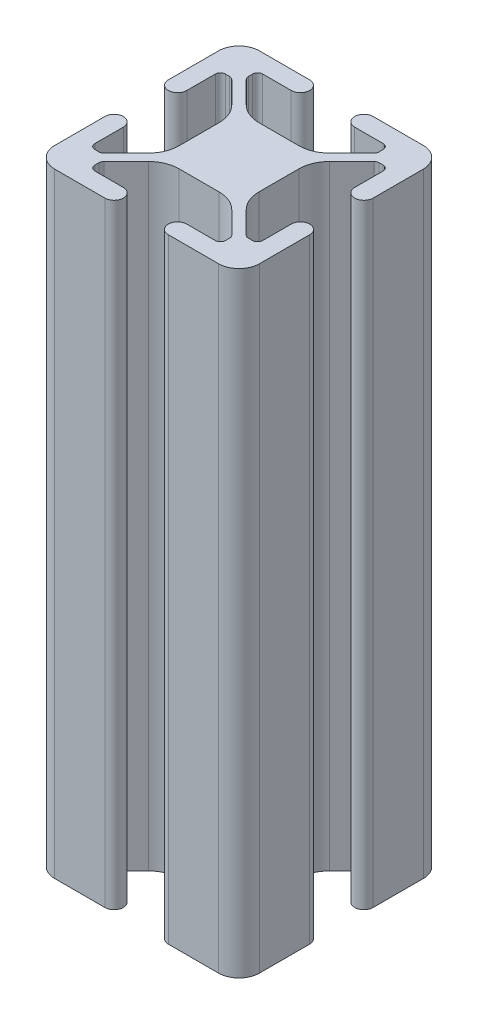
SolidWorks part; units mm, degrees
ref_plane "前视基准面" through (0, 0, 0) normal (0, 0, 1) x (1, 0, 0)
ref_plane "上视基准面" through (0, 0, 0) normal (0, 1, 0) x (1, 0, 0)
ref_plane "右视基准面" through (0, 0, 0) normal (1, 0, 0) x (0, 0, -1)
sketch "草图1" plane through (0, 0, 0) normal (0, 1, 0) x (1, 0, 0)
  line L0 (-1.0428, -10.0859) -> (3.8572, -10.0859)
  line L1 (1.0762, -11.8859) -> (3.8572, -11.8859)
  line L2 (2.8854, -15.3072) -> (0.7226, -13.1443)
  line L3 (2.1786, -16.0141) -> (0.0157, -13.8512)
  line L4 (-3.0428, -12.0859) -> (-3.0428, -16.9859)
  line L5 (-1.2428, -14.2048) -> (-1.2428, -16.9859)
  line L6 (-0.7428, -13.7048) -> (-0.3378, -13.7048)
  line L7 (0.5762, -12.3859) -> (0.5762, -12.7908)
  line L8 (-1.0428, -30.0859) -> (3.8572, -30.0859)
  line L9 (1.0762, -28.2859) -> (3.8572, -28.2859)
  line L10 (2.8854, -24.8645) -> (0.7226, -27.0274)
  line L11 (2.1786, -24.1577) -> (0.0157, -26.3205)
  line L12 (-3.0428, -28.0859) -> (-3.0428, -23.1859)
  line L13 (-1.2428, -25.9669) -> (-1.2428, -23.1859)
  line L14 (-0.7428, -26.4669) -> (-0.3378, -26.4669)
  line L15 (0.5762, -27.7859) -> (0.5762, -27.3809)
  line L16 (14.9572, -10.0859) -> (10.0572, -10.0859)
  line L17 (12.8383, -11.8859) -> (10.0572, -11.8859)
  line L18 (11.029, -15.3072) -> (13.1919, -13.1443)
  line L19 (11.7359, -16.0141) -> (13.8988, -13.8512)
  line L20 (16.9572, -12.0859) -> (16.9572, -16.9859)
  line L21 (15.1572, -14.2048) -> (15.1572, -16.9859)
  line L22 (14.6572, -13.7048) -> (14.2523, -13.7048)
  line L23 (13.3383, -12.3859) -> (13.3383, -12.7908)
  line L24 (14.9572, -30.0859) -> (10.0572, -30.0859)
  line L25 (12.8383, -28.2859) -> (10.0572, -28.2859)
  line L26 (11.029, -24.8645) -> (13.1919, -27.0274)
  line L27 (11.7359, -24.1577) -> (13.8988, -26.3205)
  line L28 (16.9572, -28.0859) -> (16.9572, -23.1859)
  line L29 (15.1572, -25.9669) -> (15.1572, -23.1859)
  line L30 (14.6572, -26.4669) -> (14.2523, -26.4669)
  line L31 (13.3383, -27.7859) -> (13.3383, -27.3809)
  line L32 (5.0068, -16.1859) -> (8.9077, -16.1859)
  line L33 (10.8572, -18.1354) -> (10.8572, -22.0363)
  line L34 (3.0572, -18.1354) -> (3.0572, -22.0363)
  line L35 (5.0068, -23.9859) -> (8.9077, -23.9859)
  circle A0 centre (6.9572, -20.0859) radius 2.5
  arc A1 (2.8854, -15.3072) -> (5.0068, -16.1859) centre (5.0068, -13.1859) ccw
  arc A2 (3.0572, -18.1354) -> (2.1786, -16.0141) centre (0.0572, -18.1354) ccw
  arc A3 (3.8572, -11.8859) -> (3.8572, -10.0859) centre (3.8572, -10.9859) ccw
  arc A4 (0.5762, -12.7908) -> (0.7226, -13.1443) centre (1.0762, -12.7908) ccw
  arc A5 (0.0157, -13.8512) -> (-0.3378, -13.7048) centre (-0.3378, -14.2048) ccw
  arc A6 (-3.0428, -16.9859) -> (-1.2428, -16.9859) centre (-2.1428, -16.9859) ccw
  arc A7 (-1.0428, -10.0859) -> (-3.0428, -12.0859) centre (-1.0428, -12.0859) ccw
  arc A8 (-0.7428, -13.7048) -> (-1.2428, -14.2048) centre (-0.7428, -14.2048) ccw
  arc A9 (1.0762, -11.8859) -> (0.5762, -12.3859) centre (1.0762, -12.3859) ccw
  arc A10 (5.0068, -23.9859) -> (2.8854, -24.8645) centre (5.0068, -26.9859) ccw
  arc A11 (2.1786, -24.1577) -> (3.0572, -22.0363) centre (0.0572, -22.0363) ccw
  arc A12 (3.8572, -30.0859) -> (3.8572, -28.2859) centre (3.8572, -29.1859) ccw
  arc A13 (0.7226, -27.0274) -> (0.5762, -27.3809) centre (1.0762, -27.3809) ccw
  arc A14 (-0.3378, -26.4669) -> (0.0157, -26.3205) centre (-0.3378, -25.9669) ccw
  arc A15 (-1.2428, -23.1859) -> (-3.0428, -23.1859) centre (-2.1428, -23.1859) ccw
  arc A16 (-3.0428, -28.0859) -> (-1.0428, -30.0859) centre (-1.0428, -28.0859) ccw
  arc A17 (-1.2428, -25.9669) -> (-0.7428, -26.4669) centre (-0.7428, -25.9669) ccw
  arc A18 (0.5762, -27.7859) -> (1.0762, -28.2859) centre (1.0762, -27.7859) ccw
  arc A19 (8.9077, -16.1859) -> (11.029, -15.3072) centre (8.9077, -13.1859) ccw
  arc A20 (11.7359, -16.0141) -> (10.8572, -18.1354) centre (13.8572, -18.1354) ccw
  arc A21 (10.0572, -10.0859) -> (10.0572, -11.8859) centre (10.0572, -10.9859) ccw
  arc A22 (13.1919, -13.1443) -> (13.3383, -12.7908) centre (12.8383, -12.7908) ccw
  arc A23 (14.2523, -13.7048) -> (13.8988, -13.8512) centre (14.2523, -14.2048) ccw
  arc A24 (15.1572, -16.9859) -> (16.9572, -16.9859) centre (16.0572, -16.9859) ccw
  arc A25 (16.9572, -12.0859) -> (14.9572, -10.0859) centre (14.9572, -12.0859) ccw
  arc A26 (15.1572, -14.2048) -> (14.6572, -13.7048) centre (14.6572, -14.2048) ccw
  arc A27 (13.3383, -12.3859) -> (12.8383, -11.8859) centre (12.8383, -12.3859) ccw
  arc A28 (11.029, -24.8645) -> (8.9077, -23.9859) centre (8.9077, -26.9859) ccw
  arc A29 (10.8572, -22.0363) -> (11.7359, -24.1577) centre (13.8572, -22.0363) ccw
  arc A30 (10.0572, -28.2859) -> (10.0572, -30.0859) centre (10.0572, -29.1859) ccw
  arc A31 (13.3383, -27.3809) -> (13.1919, -27.0274) centre (12.8383, -27.3809) ccw
  arc A32 (13.8988, -26.3205) -> (14.2523, -26.4669) centre (14.2523, -25.9669) ccw
  arc A33 (16.9572, -23.1859) -> (15.1572, -23.1859) centre (16.0572, -23.1859) ccw
  arc A34 (14.9572, -30.0859) -> (16.9572, -28.0859) centre (14.9572, -28.0859) ccw
  arc A35 (14.6572, -26.4669) -> (15.1572, -25.9669) centre (14.6572, -25.9669) ccw
  arc A36 (12.8383, -28.2859) -> (13.3383, -27.7859) centre (12.8383, -27.7859) ccw
extrude "凸台-拉伸1" add sketch "草图1" along normal blind 60 contours L32 A19 L18 A22 L23 A27 L17 A21 L16 A25 L20 A24 L21 A26 L22 A23 L19 A20 L33 A29 L27 A32 L30 A35 L29 A33 L28 A34 L24 A30 L25 A36 L31 A31 L26 A28 L35 A10 L10 A13 L15 A18 L9 A12 L8 A16 L12 A15 L13 A17 L14 A14 L11 A11 L34 A2 L3 A5 L6 A8 L5 A6 L4 A7 L0 A3 L1 A9 L7 A4 L2 A1
ref_plane "基准面1" through (0, 30, 0) normal (0, 1, 0) x (1, 0, 0)
ref_plane "基准面2" through (6.9572, 0, 0) normal (-1, 0, 0) x (0, 0, 1)
